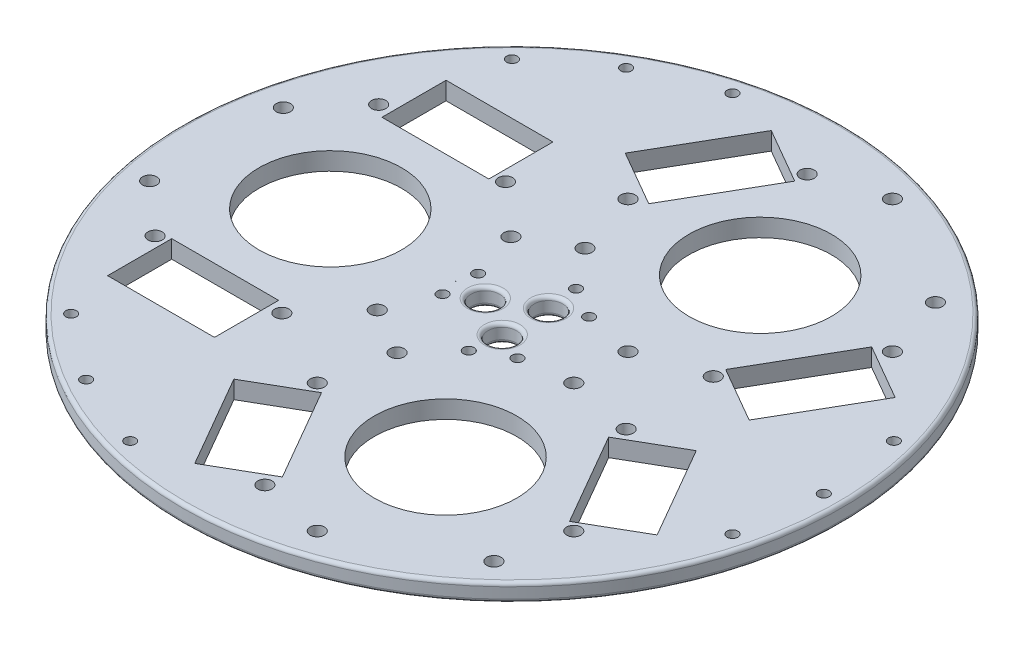
SolidWorks part; units mm, degrees
ref_plane "Front Plane" through (0, 0, 0) normal (0, 0, 1) x (1, 0, 0)
ref_plane "Top Plane" through (0, 0, 0) normal (0, 1, 0) x (1, 0, 0)
ref_plane "Right Plane" through (0, 0, 0) normal (1, 0, 0) x (0, 0, -1)
sketch "Sketch1" plane through (0, 0, 0) normal (0, 1, 0) x (1, 0, 0)
  line L0 (0, 0) -> (-51, -0.0043)
  line L11 (-51, -0.0043) -> (-87, -0.0043)
  line L12 (-51, -0.0043) -> (-82.1769, 17.9957)
  line L13 (-51, -0.0043) -> (-69, 31.1726)
  line L14 (-51, -0.0043) -> (-51, 35.9957)
  line L15 (-51, -0.0043) -> (-33, 31.1726)
  line L16 (-51, -0.0043) -> (-19.8231, 17.9957)
  line L17 (-51, -0.0043) -> (-15, -0.0043)
  line L18 (-51, -0.0043) -> (-19.8231, -18.0043)
  line L19 (-51, -0.0043) -> (-33, -31.1812)
  line L20 (-51, -0.0043) -> (-51, -36.0043)
  line L21 (-51, -0.0043) -> (-69, -31.1812)
  line L22 (-51, -0.0043) -> (-82.1769, -18.0043)
  line L23 (-51, -0.0043) -> (-83.31, -0.0043)
  line L24 (-51, -0.0043) -> (-78.9813, -16.1593)
  line L25 (-51, -0.0043) -> (-83.1382, -18.5593)
  circle A1 centre (-51, -0.0043) radius 32.31
  circle A2 centre (-51, -0.0043) radius 36
  circle A3 centre (-82.1769, 17.9957) radius 2
  circle A4 centre (-33, 31.1726) radius 2
  circle A5 centre (-19.8231, -18.0043) radius 2
  circle A6 centre (-69, -31.1812) radius 2
  circle A7 centre (-83.1382, -18.5593) radius 2
  circle A8 centre (-69.555, 32.1339) radius 2
  circle A9 centre (-18.8618, 18.5507) radius 2
  circle A10 centre (-32.445, -32.1425) radius 2
  circle A11 centre (-51, -0.0043) radius 20
  circle A35 centre (0, 0) radius 92.5
  circle A36 centre (-11.6137, 44.1694) radius 2
  circle A37 centre (-5.6806, 26.1694) radius 2
  circle A38 centre (7.4963, 75.3463) radius 2
  circle A39 centre (25.4963, 81.2794) radius 2
  circle A40 centre (56.6732, 62.1694) radius 2
  circle A41 centre (62.6063, 44.1694) radius 2
  circle A42 centre (43.4963, 12.9925) radius 2
  circle A43 centre (25.4963, 7.0594) radius 2
  circle A44 centre (25.4963, 44.1694) radius 20
  circle A45 centre (44.0587, -12.027) radius 2
  circle A46 centre (25.5037, -8.1652) radius 2
  circle A47 centre (61.5037, -44.1652) radius 2
  circle A48 centre (57.6419, -62.7202) radius 2
  circle A49 centre (25.5037, -80.1652) radius 2
  circle A50 centre (6.9487, -76.3034) radius 2
  circle A51 centre (-10.4963, -44.1652) radius 2
  circle A52 centre (-6.6345, -25.6102) radius 2
  circle A53 centre (25.5037, -44.1652) radius 20
  point P24 (-51, -0.0043)
  point P33 (-51, -0.0043)
  point P36 (-51, -0.0043)
  point P44 (-51, -0.0043)
  point P78 (0, 0)
  dimension "D3" = 51
  dimension "D4" = 64.62
  dimension "D5" = 36
  dimension "D7" = 30
  dimension "D8" = 4
  dimension "D9" = 72
  dimension "D10" = 4
  dimension "D11" = 4
  dimension "D12" = 40
  dimension "D2" = 37.11
  dimension "D13" = 185
  dimension "D14" = 3
  dimension "D6" = 12
extrude "Boss-Extrude1" add sketch "Sketch1" along normal blind 5
sketch "Sketch4" plane through (0, 5, 0) normal (0, 1, 0) x (1, 0, 0)
  line L0 (-51, -0.0043) -> (-51, 29.4957)
  line L6 (-51, 29.4957) -> (-66, 29.4957)
  line L12 (-51, 29.4957) -> (-36, 29.4957)
  line L13 (-66, 29.4957) -> (-66, 47.4957)
  line L14 (-66, 47.4957) -> (-36, 47.4957)
  line L15 (-36, 47.4957) -> (-36, 29.4957)
  line L16 (-18.69, -0.0043) -> (-15, -0.0043) construction
  line L17 (-66, -47.5043) -> (-36, -47.5043)
  line L18 (-66, -29.5043) -> (-66, -47.5043)
  line L19 (-51, -29.5043) -> (-66, -29.5043)
  line L20 (-36, -47.5043) -> (-36, -29.5043)
  line L21 (-51, -29.5043) -> (-36, -29.5043)
  line L22 (-8.1399, 80.9098) -> (-23.1399, 54.9291)
  line L23 (7.4485, 71.9098) -> (-8.1399, 80.9098)
  line L24 (-0.0515, 58.9194) -> (7.4485, 71.9098)
  line L25 (-23.1399, 54.9291) -> (-7.5515, 45.9291)
  line L26 (-0.0515, 58.9194) -> (-7.5515, 45.9291)
  line L27 (58.544, 42.4098) -> (74.1325, 33.4098)
  line L28 (74.1325, 33.4098) -> (59.1325, 7.4291)
  line L29 (59.1325, 7.4291) -> (43.544, 16.4291)
  line L30 (51.044, 29.4194) -> (43.544, 16.4291)
  line L31 (51.044, 29.4194) -> (58.544, 42.4098)
  line L32 (74.1399, -33.4055) -> (59.1399, -7.4248)
  line L33 (58.5515, -42.4055) -> (74.1399, -33.4055)
  line L34 (51.0515, -29.4152) -> (58.5515, -42.4055)
  line L35 (59.1399, -7.4248) -> (43.5515, -16.4248)
  line L36 (51.0515, -29.4152) -> (43.5515, -16.4248)
  line L37 (7.456, -71.9055) -> (-8.1325, -80.9055)
  line L38 (-8.1325, -80.9055) -> (-23.1325, -54.9248)
  line L39 (-23.1325, -54.9248) -> (-7.544, -45.9248)
  line L40 (-0.044, -58.9152) -> (-7.544, -45.9248)
  line L41 (-0.044, -58.9152) -> (7.456, -71.9055)
  point P37 (0, 0)
  dimension "D1" = 29.5
  dimension "D2" = 18
  dimension "D3" = 30
  dimension "D4" = 90
  dimension "D5" = 15
  dimension "D6" = 3
extrude "Cut-Extrude5" cut sketch "Sketch4" against normal blind 5
sketch "Sketch7" plane through (0, 5, 0) normal (0, 1, 0) x (1, 0, 0)
  line L1 (0, 0) -> (-51, -0.0043)
  circle A0 centre (-51, -0.0043) radius 42.5
  circle A1 centre (25.4963, 44.1694) radius 42.5
  circle A2 centre (25.5037, -44.1652) radius 42.5
  point P12 (0, 0)
  dimension "D1" = 3
sketch "Sketch8" plane through (0, 5, 0) normal (0, 1, 0) x (1, 0, 0)
  line L2 (0, 0) -> (-43.7564, 75.7736)
  line L3 (0, 0) -> (-51, -0.0043) construction
  circle A1 centre (-43.7564, 75.7736) radius 1.5
  circle A2 centre (-22.6538, 84.5166) radius 1.5
  circle A3 centre (-61.877, 61.8667) radius 1.5
  circle A4 centre (87.5, 0.0073) radius 1.5
  circle A5 centre (84.5166, 22.6538) radius 1.5
  circle A6 centre (84.5204, -22.6396) radius 1.5
  circle A7 centre (-43.7436, -75.7809) radius 1.5
  circle A8 centre (-22.6396, -84.5204) radius 1.5
  circle A9 centre (-61.8667, -61.877) radius 1.5
  point P10 (0, 0)
  point P12 (0, 0)
  point P18 (0, 0)
  point P28 (0, 0)
  dimension "D3" = 2
  dimension "D4" = 3
  dimension "D2" = 2
  dimension "D1" = 60
  dimension "87.5" = 87.5
extrude "Cut-Extrude6" cut sketch "Sketch8" against normal through all
fillet "Fillet2" radius 1 2 edges at (0, 5, 92.5) (0, 0, 92.5)
sketch "Sketch9" plane through (0, 5, 0) normal (0, 1, 0) x (1, 0, 0)
  line L0 (0, 0) -> (-7.5, 0)
  dimension "D1" = 7.5
sketch "Sketch10" plane through (0, 5, 0) normal (0, 1, 0) x (1, 0, 0)
  circle A0 centre (-7.5, 0) radius 4
  circle A1 centre (3.7495, 6.4955) radius 4
  circle A2 centre (3.75, -6.4946) radius 4
  point P9 (-0.0002, 0.0003)
  dimension "D1" = 3
  dimension "D2" = 8
extrude "Cut-Extrude7" cut sketch "Sketch10" against normal blind 10
fillet "Fillet3" radius 1 6 edges at (3.75, 5, 10.4946) (3.75, 0, 10.4946) (3.7495, 5, -2.4955) (3.7495, 0, -2.4955) (-7.5, 5, 4) (-7.5, 0, 4)
sketch "Sketch12" plane through (0, 0, 0) normal (0, -1, 0) x (1, 0, 0)
  line L0 (0, 0) -> (-14.5, 0.0012)
  line L1 (0, 0) -> (-51, 0.0043) construction
  line L2 (-14.5, 4.9982) -> (-14.5, -4.9957)
  circle A0 centre (2.9162, -15.0595) radius 1.5
  circle A1 centre (11.5764, -10.0595) radius 1.5
  circle A2 centre (11.5838, 10.0552) radius 1.5
  circle A3 centre (2.9236, 15.0552) radius 1.5
  circle A4 centre (-14.5, 4.9982) radius 1.5
  circle A5 centre (-14.5, -4.9957) radius 1.5
  point P26 (-14.5, 0.0012)
  dimension "D1" = 3
extrude "Cut-Extrude8" cut sketch "Sketch12" against normal through all
